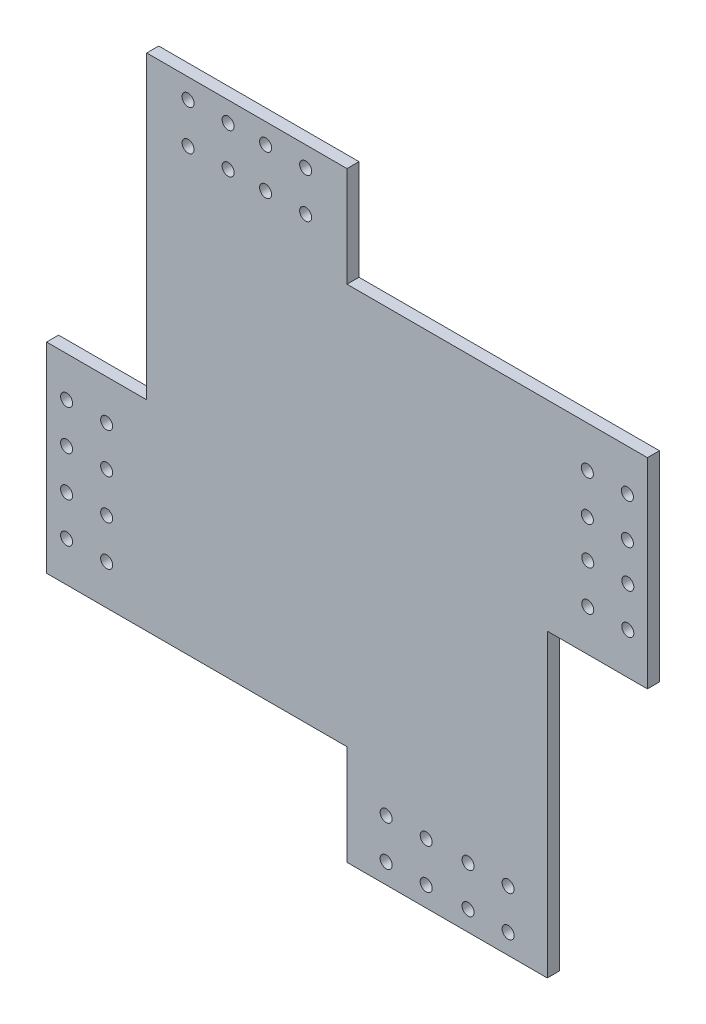
SolidWorks part; units mm, degrees
ref_plane "정면" through (0, 0, 0) normal (0, 0, 1) x (1, 0, 0)
ref_plane "윗면" through (0, 0, 0) normal (0, 1, 0) x (1, 0, 0)
ref_plane "우측면" through (0, 0, 0) normal (1, 0, 0) x (0, 0, -1)
sketch "스케치1" plane through (0, 0, 0) normal (0, 0, 1) x (1, 0, 0)
  line L0 (50, -25) -> (50, -75)
  line L1 (-50, -75) -> (0, -75)
  line L2 (-50, 25) -> (-50, -25)
  line L4 (75, 25) -> (0, 25)
  line L5 (50, -75) -> (-50, 25) construction
  line L6 (50, 25) -> (-50, -75) construction
  line L8 (-50, 25) -> (-50, 50)
  line L9 (-50, 50) -> (0, 50)
  line L10 (0, 25) -> (0, 50)
  line L13 (50, -25) -> (75, -25)
  line L14 (75, 25) -> (75, -25)
  line L16 (50, -75) -> (50, -100)
  line L17 (50, -100) -> (0, -100)
  line L18 (0, -75) -> (0, -100)
  line L19 (-50, -75) -> (-75, -75)
  line L21 (-50, -25) -> (-75, -25)
  line L22 (-75, -75) -> (-75, -25)
  line L29 (25, -80) -> (25, -100) construction
  line L53 (-75, -50) -> (-55, -50) construction
  circle A4 centre (70.1062, -4.68) radius 1.5
  circle A5 centre (60.1062, -4.68) radius 1.5
  circle A6 centre (70.1062, -14.68) radius 1.5
  circle A7 centre (60.1062, -14.68) radius 1.5
  circle A8 centre (9.7733, -85) radius 1.5
  circle A9 centre (19.7733, -85) radius 1.5
  circle A10 centre (9.7733, -95) radius 1.5
  circle A11 centre (19.7733, -95) radius 1.5
  circle A12 centre (40.2267, -95) radius 1.5
  circle A13 centre (30.2267, -95) radius 1.5
  circle A14 centre (30.2267, -85) radius 1.5
  circle A15 centre (40.2267, -85) radius 1.5
  circle A16 centre (-39.6803, 45) radius 1.5
  circle A17 centre (-29.6803, 45) radius 1.5
  circle A18 centre (-39.6803, 35) radius 1.5
  circle A19 centre (-29.6803, 35) radius 1.5
  circle A20 centre (-10.3197, 35) radius 1.5
  circle A21 centre (-20.3197, 35) radius 1.5
  circle A22 centre (-20.3197, 45) radius 1.5
  circle A23 centre (-10.3197, 45) radius 1.5
  circle A36 centre (70, 14.68) radius 1.5
  circle A37 centre (60, 14.68) radius 1.5
  circle A38 centre (70, 4.68) radius 1.5
  circle A39 centre (60, 4.68) radius 1.5
  circle A40 centre (-70, -35) radius 1.5
  circle A41 centre (-60, -35) radius 1.5
  circle A42 centre (-70, -45) radius 1.5
  circle A43 centre (-60, -45) radius 1.5
  circle A44 centre (-60, -55) radius 1.5
  circle A45 centre (-70, -55) radius 1.5
  circle A46 centre (-60, -65) radius 1.5
  circle A47 centre (-70, -65) radius 1.5
  point P0 (0, 0)
  point P48 (25, -90)
  point P53 (9.7733, -85)
  point P54 (19.7733, -85)
  point P55 (9.7733, -95)
  point P56 (19.7733, -95)
  dimension "D24" = 25
  dimension "D25" = 25
  dimension "D26" = 25
  dimension "D27" = 10
  dimension "D48" = 3
  dimension "D49" = 3
  dimension "D50" = 3
  dimension "D51" = 3
  dimension "D13" = 10
  dimension "D2" = 10.3197
  dimension "D3" = 10.32
  dimension "D4" = 50
  dimension "D5" = 25
  dimension "D6" = 50
  dimension "D7" = 50
  dimension "D8" = 25
  dimension "D10" = 50
  dimension "D11" = 10.32
  dimension "D12" = 100
  dimension "D14" = 100
  dimension "D15" = 10.3197
  dimension "D16" = 10
  dimension "D17" = 9.3607
  dimension "D18" = 9.36
  dimension "D19" = 10
  dimension "D20" = 10
  dimension "D21" = 10
  dimension "D22" = 25
  dimension "D23" = 25
  dimension "D28" = 0
  dimension "D29" = 0
  dimension "D30" = 0
  dimension "D31" = 0
  dimension "D32" = 0
  dimension "D53" = 10
  dimension "D54" = 10
  dimension "D56" = 10
extrude "보스-돌출4" add sketch "스케치1" along normal blind 3
